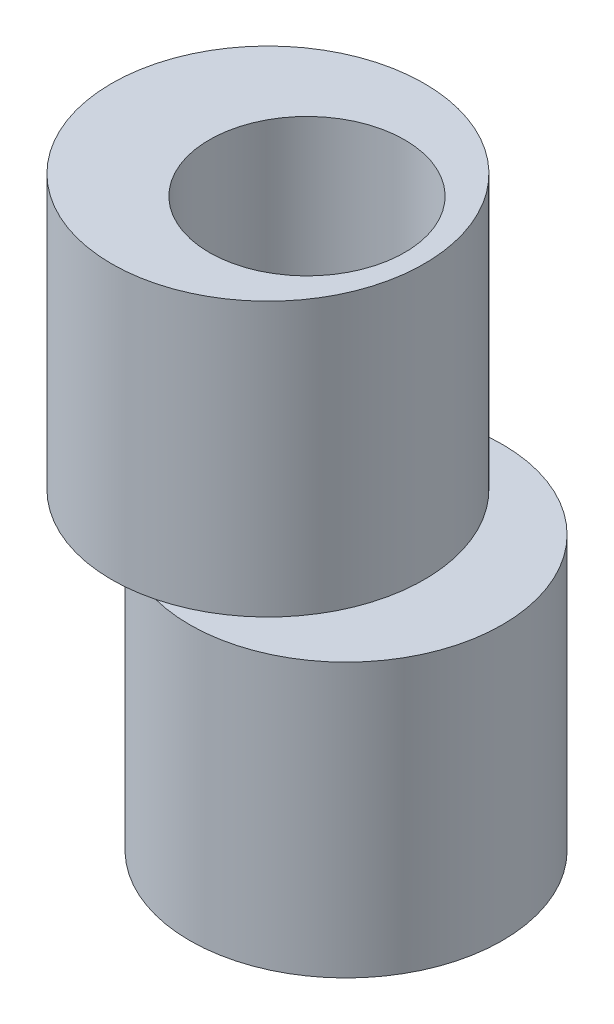
SolidWorks part; units mm, degrees
ref_plane "Front Plane" through (0, 0, 0) normal (0, 0, 1) x (1, 0, 0)
ref_plane "Top Plane" through (0, 0, 0) normal (0, 1, 0) x (1, 0, 0)
ref_plane "Right Plane" through (0, 0, 0) normal (1, 0, 0) x (0, 0, -1)
sketch "Sketch2" plane through (0, 0, 0) normal (0, 1, 0) x (1, 0, 0)
  line L0 (0, 0) -> (1, 0) construction
  circle A0 centre (0, 0) radius 2.5
  circle A1 centre (1, 0) radius 4
  dimension "D1" = 5
  dimension "D3" = 8
  dimension "D2" = 1
extrude "Boss-Extrude1" add sketch "Sketch2" along normal blind 7
sketch "Sketch3" plane through (0, 7, 0) normal (0, 1, 0) x (1, 0, 0)
  line L0 (0, 0) -> (-1, 0) construction
  circle A0 centre (-1, 0) radius 4
  circle A1 centre (0, 0) radius 2.5 construction
  circle A2 centre (0, 0) radius 2.5
  dimension "D2" = 8
  dimension "D1" = 1
extrude "Boss-Extrude2" add sketch "Sketch3" along normal blind 7
